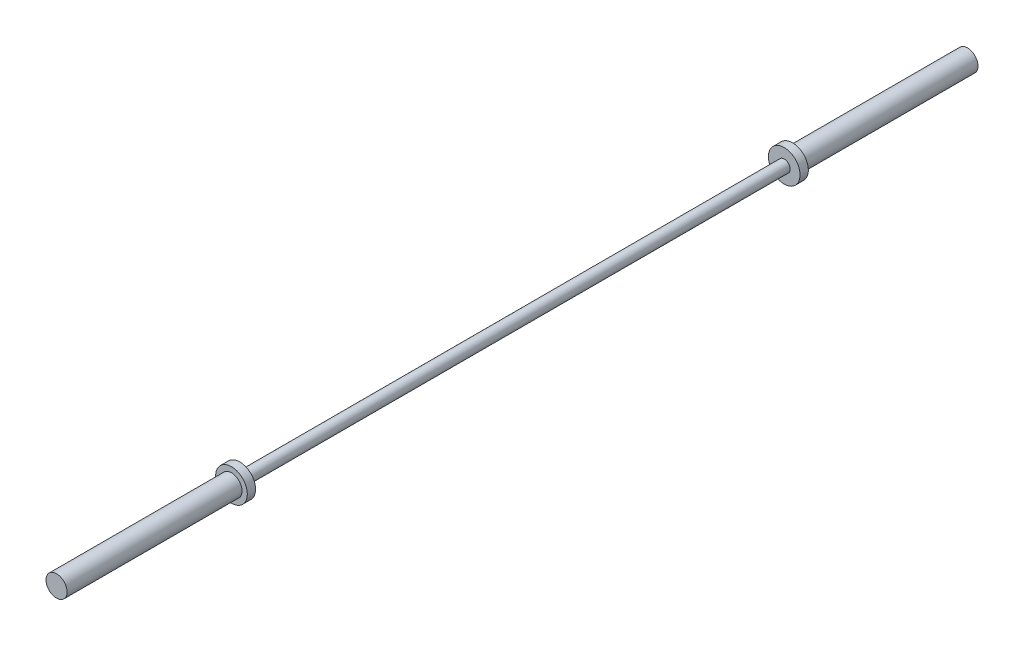
SolidWorks part; units mm, degrees
ref_plane "Front Plane" through (0, 0, 0) normal (0, 0, 1) x (1, 0, 0)
ref_plane "Top Plane" through (0, 0, 0) normal (0, 1, 0) x (1, 0, 0)
ref_plane "Right Plane" through (0, 0, 0) normal (1, 0, 0) x (0, 0, -1)
sketch "Sketch1" plane through (0, 0, 0) normal (1, 0, 0) x (0, 0, -1)
  line L0 (0, 0) -> (-1100, 0)
  line L1 (0, 0) -> (1100, 0)
  line L6 (0, 14.25) -> (-657.5, 14.25)
  line L7 (-677.5, 25.5) -> (-1100, 25.5)
  line L8 (-657.5, 38.25) -> (-657.5, 14.25)
  line L9 (-1100, 25.5) -> (-1100, 0)
  line L10 (657.5, 14.25) -> (657.5, 38.25)
  line L11 (-657.5, 38.25) -> (-677.5, 38.25)
  line L12 (-677.5, 38.25) -> (-677.5, 25.5)
  line L13 (0, 14.25) -> (657.5, 14.25)
  line L14 (657.5, 38.25) -> (677.5, 38.25)
  line L15 (677.5, 38.25) -> (677.5, 25.5)
  line L16 (677.5, 25.5) -> (1100, 25.5)
  line L17 (1100, 25.5) -> (1100, 0)
revolve "Revolve1" add sketch "Sketch1" angle 360 about L1
